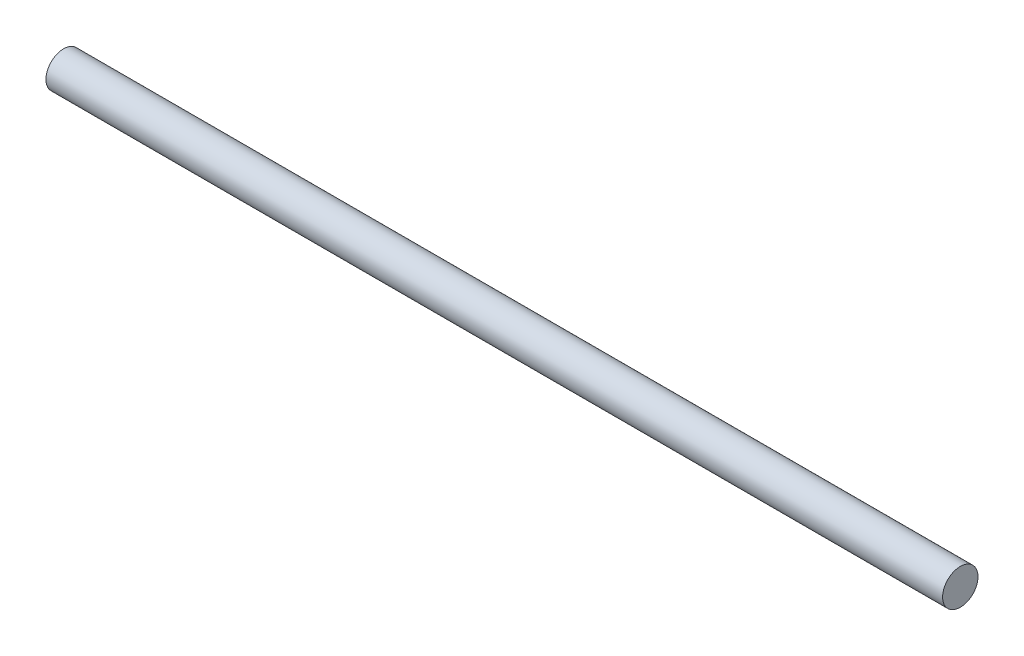
SolidWorks part; units mm, degrees
material "AISI 316 Stainless Steel Sheet (SS)"
ref_plane "Front Plane" through (0, 0, 0) normal (0, 0, 1) x (1, 0, 0)
ref_plane "Top Plane" through (0, 0, 0) normal (0, 1, 0) x (1, 0, 0)
ref_plane "Right Plane" through (0, 0, 0) normal (1, 0, 0) x (0, 0, -1)
sketch "Sketch1" plane through (0, 0, 0) normal (1, 0, 0) x (0, 0, -1)
  circle A0 centre (0, 0) radius 2.35
  dimension "D1" = 4.7
extrude "Boss-Extrude1" add sketch "Sketch1" along normal mid plane 119
